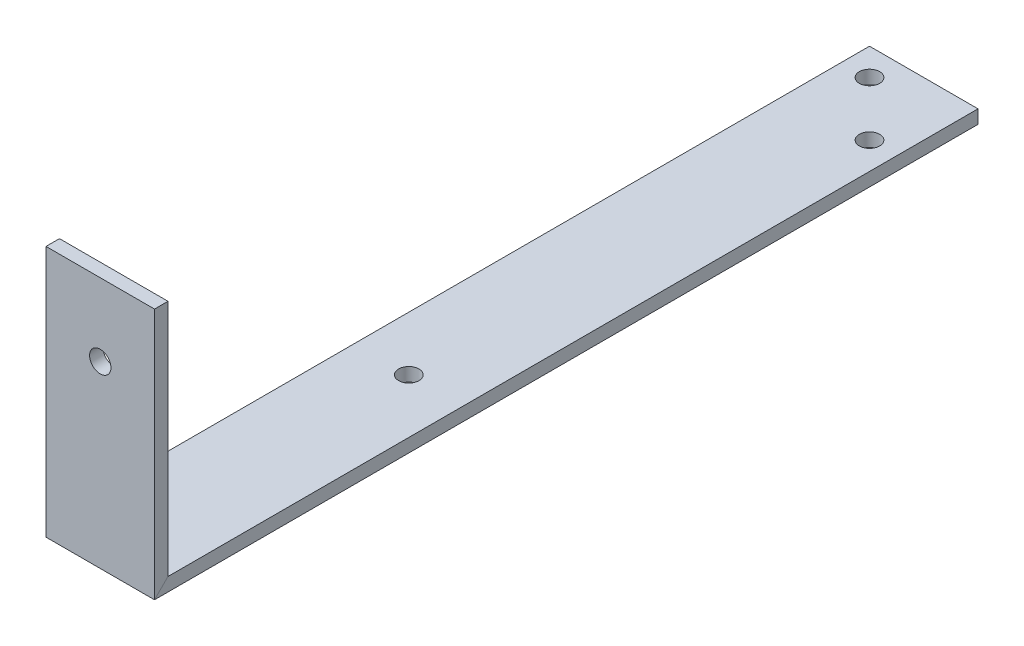
SolidWorks part; units mm, degrees
ref_plane "Alzado" through (0, 0, 0) normal (0, 0, 1) x (1, 0, 0)
ref_plane "Planta" through (0, 0, 0) normal (0, 1, 0) x (1, 0, 0)
ref_plane "Vista lateral" through (0, 0, 0) normal (1, 0, 0) x (0, 0, -1)
sketch "Croquis2" plane through (0, 0, 0) normal (0, 1, 0) x (1, 0, 0)
  line L1 (-25.4, 3.155) -> (25.4, 3.155)
  line L2 (-25.4, 3.155) -> (-25.4, -3.155)
  line L3 (-25.4, -3.155) -> (25.4, -3.155)
  line L4 (25.4, 3.155) -> (25.4, -3.155)
  line L5 (-25.4, 3.155) -> (25.4, -3.155) construction
  line L6 (-25.4, -3.155) -> (25.4, 3.155) construction
  line L7 (184.6, 3.155) -> (235.4, 3.155)
  line L8 (184.6, 3.155) -> (184.6, -3.155)
  line L9 (184.6, -3.155) -> (235.4, -3.155)
  line L10 (235.4, 3.155) -> (235.4, -3.155)
  line L11 (184.6, 3.155) -> (235.4, -3.155) construction
  line L12 (184.6, -3.155) -> (235.4, 3.155) construction
  point P0 (0, 0)
  point P6 (210, 0)
  dimension "D1" = 50.8
  dimension "D2" = 6.31
  dimension "D3" = 210
  dimension "D4" = 50.8
  dimension "D5" = 6.31
sketch3d "Croquis3D1"
  line L0 (0, 0, 0) -> (0, -567.24, 0)
  line L1 (0, -567.24, 0) -> (0, -567.24, 336.2)
  line L2 (0, -567.24, 336.2) -> (1786.7, -567.24, 336.2)
  line L3 (1786.7, -567.24, 336.2) -> (1786.7, -567.24, 693.16)
  line L4 (-25.4, 0, 0) -> (-25.4, -383.9185, 0) construction
  line L5 (-25.4, 0, -3.155) -> (-25.4, 0, 3.155) construction
  line L6 (-25.4, -383.9185, 0) -> (-25.4, -383.9185, 653.2834) construction
  line L7 (1786.7, -567.24, 693.16) -> (1786.7, -436.23, 693.16)
  line L8 (1786.7, -436.23, 693.16) -> (1786.7, -436.23, 1487.1629)
  dimension "D1" = 567.24
  dimension "D2" = 336.2
  dimension "D3" = 1786.7
  dimension "D4" = 356.96
  dimension "D5" = 131.01
  dimension "D6" = 794.0029
sweep "Barrer1" add profiles "Croquis2" path "Croquis3D1"
sketch "Croquis3" plane through (0, 0, -3.155) normal (0, 0, -1) x (-1, 0, 0)
  line L0 (-235.4, 0) -> (-235.4, -6.31)
  line L1 (-235.4, 0) -> (-235.4, -570.395) construction
  line L2 (-235.4, -6.31) -> (-184.6, -6.31)
  line L3 (-184.6, 0) -> (-184.6, -570.395) construction
  line L4 (-184.6, -6.31) -> (-184.6, 0)
  line L5 (-184.6, 0) -> (-235.4, 0)
  line L7 (-25.4, 0) -> (-25.4, -6.31)
  line L8 (-25.4, 0) -> (-25.4, -570.395) construction
  line L9 (-25.4, -6.31) -> (25.4, -6.31)
  line L10 (25.4, 0) -> (25.4, -570.395) construction
  line L11 (25.4, -6.31) -> (25.4, 0)
  line L12 (-25.4, 0) -> (25.4, 0) construction
  line L13 (25.4, 0) -> (-25.4, 0)
  dimension "D1" = 6.31
  dimension "D2" = 6.31
sketch3d "Croquis3D2"
  line L0 (25.4, -3.155, -3.155) -> (-0.201, -3.155, -3.155) construction
  line L1 (25.4, 0, -3.155) -> (25.4, -6.31, -3.155) construction
  line L2 (-0.201, -3.155, -3.155) -> (-0.201, -5.2746, -3.155) construction
  line L3 (-0.201, -3.155, -3.155) -> (-0.201, -3.155, -207.155)
  line L4 (-0.201, -3.155, -207.155) -> (-0.201, -53.155, -207.155)
  dimension "D1" = 204
  dimension "D2" = 50
sweep "Barrer4" add profiles "Croquis3" path "Croquis3D2"
sketch "Croquis4" plane through (0, 0, -210.31) normal (0, 0, -1) x (-1, 0, 0)
  line L0 (-184.6, 0) -> (-184.6, -53.155)
  line L1 (-184.6, -53.155) -> (-124.6, -53.155)
  line L2 (-124.6, -53.155) -> (-124.6, 0)
  line L3 (-124.6, 0) -> (-184.6, 0)
  dimension "D1" = 60
extrude "Saliente-Extruir1" add sketch "Croquis4" against normal blind 6.31
sketch "Croquis5" plane through (0, 0, -204) normal (0, 0, 1) x (1, 0, 0)
  line L0 (184.6, -6.31) -> (124.6, -6.31)
  line L1 (124.6, -53.155) -> (124.6, 0) construction
  line L2 (124.6, -6.31) -> (124.6, 0)
  line L3 (124.6, 0) -> (184.6, 0)
  line L4 (184.6, 0) -> (184.6, -6.31)
extrude "Cortar-Extruir1" cut sketch "Croquis5" against normal blind 6.31
sketch "Croquis6" plane through (0, -433.075, 0) normal (0, 1, 0) x (1, 0, 0)
  circle A0 centre (1285.7, -1260.295) radius 4.75
  circle A1 centre (1495.7, -1260.295) radius 4.75
sketch "Croquis7" plane through (0, 0, 0) normal (0, 1, 0) x (1, 0, 0)
  line L0 (1761.3, -361.6) -> (2022.1, -361.6)
  line L1 (2022.1, -100.8) -> (2022.1, -690.005) construction
  line L2 (2022.1, -361.6) -> (2022.1, 278.6006)
  line L3 (2022.1, 278.6006) -> (-188.1159, 278.6006)
  line L4 (-188.1159, 278.6006) -> (-188.1159, -361.6)
  line L5 (-188.1159, -361.6) -> (1761.3, -361.6)
extrude "Cortar-Extruir2" cut sketch "Croquis7" against normal blind 634
sketch "Croquis8" plane through (0, 0, 361.6) normal (0, 0, -1) x (-1, 0, 0)
  line L0 (-1812.1, -564.085) -> (-1761.3, -564.085)
  line L1 (-1761.3, -564.085) -> (-1761.3, -570.395)
  line L2 (-1761.3, -570.395) -> (-1812.1, -570.395)
  line L3 (-1812.1, -570.395) -> (-1812.1, -564.085)
extrude "Saliente-Extruir2" add sketch "Croquis8" along normal blind 63.5
sketch "Croquis9" plane through (0, -433.075, 0) normal (0, 1, 0) x (1, 0, 0)
  line L0 (1786.7, -1487.1629) -> (1996.7, -1487.1629) construction
  line L1 (1761.3, -1487.1629) -> (1812.1, -1487.1629) construction
  line L2 (1971.3, -1487.1629) -> (2022.1, -1487.1629) construction
  line L3 (1996.7, -1487.1629) -> (1996.7, -1454.1629) construction
  line L4 (1996.7, -1454.1629) -> (1996.7, -1234.1629) construction
  line L5 (1786.7, -1487.1629) -> (1786.7, -1454.1629) construction
  line L6 (1786.7, -1454.1629) -> (1786.7, -1234.1629) construction
  circle A0 centre (1786.7, -1454.1629) radius 5
  circle A1 centre (1786.7, -1234.1629) radius 5
  circle A2 centre (1996.7, -1234.1629) radius 5
  circle A3 centre (1996.7, -1454.1629) radius 5
  dimension "D3" = 10
  dimension "D4" = 10
  dimension "D5" = 10
  dimension "D6" = 10
  dimension "D1" = 33
  dimension "D2" = 220
extrude "Cortar-Extruir3" cut sketch "Croquis9" against normal blind 10
sketch "Croquis10" plane through (2022.1, 0, 0) normal (1, 0, 0) x (0, 0, -1)
  line L0 (-696.315, -439.385) -> (-696.315, -433.075)
  line L1 (-690.005, -433.075) -> (-1487.1629, -433.075) construction
  line L2 (-696.315, -433.075) -> (-1487.1629, -433.075)
  line L3 (-1487.1629, -433.075) -> (-1487.1629, -439.385)
  line L4 (-1487.1629, -439.385) -> (-696.315, -439.385)
extrude "Cortar-Extruir4" cut sketch "Croquis10" against normal blind 286
sketch "Croquis11" plane through (0, -433.075, 0) normal (0, 1, 0) x (1, 0, 0)
  line L0 (2022.1, -696.315) -> (2022.1, -690.005)
  line L1 (2022.1, -690.005) -> (1761.3, -690.005)
  line L2 (1761.3, -690.005) -> (1761.3, -696.315)
  line L3 (1761.3, -696.315) -> (2022.1, -696.315)
  line L4 (2022.1, -696.315) -> (2028.4123, -762.8726)
  line M1 (1971.3, -690.005) -> (1971.3, -696.315)
  line M2 (1971.3, -696.315) -> (2022.1, -696.315)
  line M3 (2022.1, -696.315) -> (2022.1, -690.005)
  line M4 (2022.1, -690.005) -> (1971.3, -690.005)
extrude "Cortar-Extruir5" cut sketch "Croquis11" against normal blind 13.11 contours M4 M1 M2 M3 | L2 L3 L1 M1
sketch "Croquis12" plane through (0, 0, 361.6) normal (0, 0, -1) x (-1, 0, 0)
  line L0 (-2022.1, -564.085) -> (-2022.1, -570.395)
  line L1 (-2022.1, -570.395) -> (-1971.3, -570.395)
  line L2 (-1971.3, -570.395) -> (-1971.3, -564.085)
  line L3 (-1971.3, -564.085) -> (-2022.1, -564.085)
extrude "Saliente-Extruir3" add sketch "Croquis12" along normal blind 6.35
sketch "Croquis13" plane through (0, -564.085, 0) normal (0, 1, 0) x (1, 0, 0)
  line L0 (1812.1, -298.1) -> (1812.1, -304.45)
  line L1 (1812.1, -298.1) -> (1812.1, -690.005) construction
  line L2 (1812.1, -304.45) -> (1761.3, -304.45)
  line L3 (1761.3, -298.1) -> (1761.3, -690.005) construction
  line L4 (1761.3, -304.45) -> (1761.3, -298.1)
  line L5 (1761.3, -298.1) -> (1812.1, -298.1)
  dimension "D1" = 6.35
extrude "Cortar-Extruir6" cut sketch "Croquis13" against normal blind 6.35
sketch "Croquis14" plane through (0, -446.185, 0) normal (0, 1, 0) x (1, 0, 0)
  line L0 (1761.3, -696.315) -> (1761.3, -690.005)
  line L1 (1761.3, -690.005) -> (2022.1, -690.005)
  line L2 (2022.1, -690.005) -> (2022.1, -696.315)
  line L3 (2022.1, -696.315) -> (1761.3, -696.315)
extrude "Cortar-Extruir7" cut sketch "Croquis14" against normal blind 6.31
sketch "Croquis15" plane through (0, 0, 304.45) normal (0, 0, -1) x (-1, 0, 0)
  line L0 (-1812.1, -564.085) -> (-1812.1, -570.395)
  line L1 (-1812.1, -570.395) -> (-1761.3, -570.395)
  line L2 (-1761.3, -570.395) -> (-1761.3, -564.085)
  line L3 (-1761.3, -564.085) -> (-1812.1, -564.085)
extrude "Cortar-Extruir8" cut sketch "Croquis15" against normal blind 6.31
sketch "Croquis16" plane through (0, -452.495, 0) normal (0, 1, 0) x (1, 0, 0)
  line L1 (2033.1978, -330.6694) -> (1954.4214, -330.6694)
  line L2 (2033.1978, -330.6694) -> (2033.1978, -785.1486)
  line L3 (2033.1978, -785.1486) -> (1954.4214, -785.1486)
  line L4 (1954.4214, -330.6694) -> (1954.4214, -785.1486)
  line L5 (2033.1978, -330.6694) -> (1954.4214, -785.1486) construction
  line L6 (2033.1978, -785.1486) -> (1954.4214, -330.6694) construction
  point P0 (1993.8096, -557.909)
extrude "Cortar-Extruir9" cut sketch "Croquis16" against normal blind 128
sketch "Croquis22" plane through (0, -564.085, 0) normal (0, 1, 0) x (1, 0, 0)
  line L0 (1786.7, -690.005) -> (1786.7, -551.855) construction
  line L1 (1812.1, -690.005) -> (1761.3, -690.005) construction
  line L2 (1786.7, -336.2) -> (1786.7, -693.16) construction
  circle A0 centre (1786.7, -551.855) radius 4.7625
  dimension "D2" = 9.525
  dimension "D1" = 138.15
extrude "Cortar-Extruir15" cut sketch "Croquis22" against normal blind 33
sketch "Croquis24" plane through (0, 0, 690.005) normal (0, 0, -1) x (-1, 0, 0)
  circle A0 centre (-1786.7, -486.4987) radius 5
extrude "Cortar-Extruir18" cut sketch "Croquis24" against normal blind 33
sketch "Croquis25" plane through (0, -570.395, 0) normal (0, -1, 0) x (-1, 0, 0)
  circle A0 centre (-1799.4, -348.8622) radius 4.7625
  circle A1 centre (-1774, -323.4622) radius 4.7625
extrude "Cortar-Extruir19" cut sketch "Croquis25" against normal blind 50
